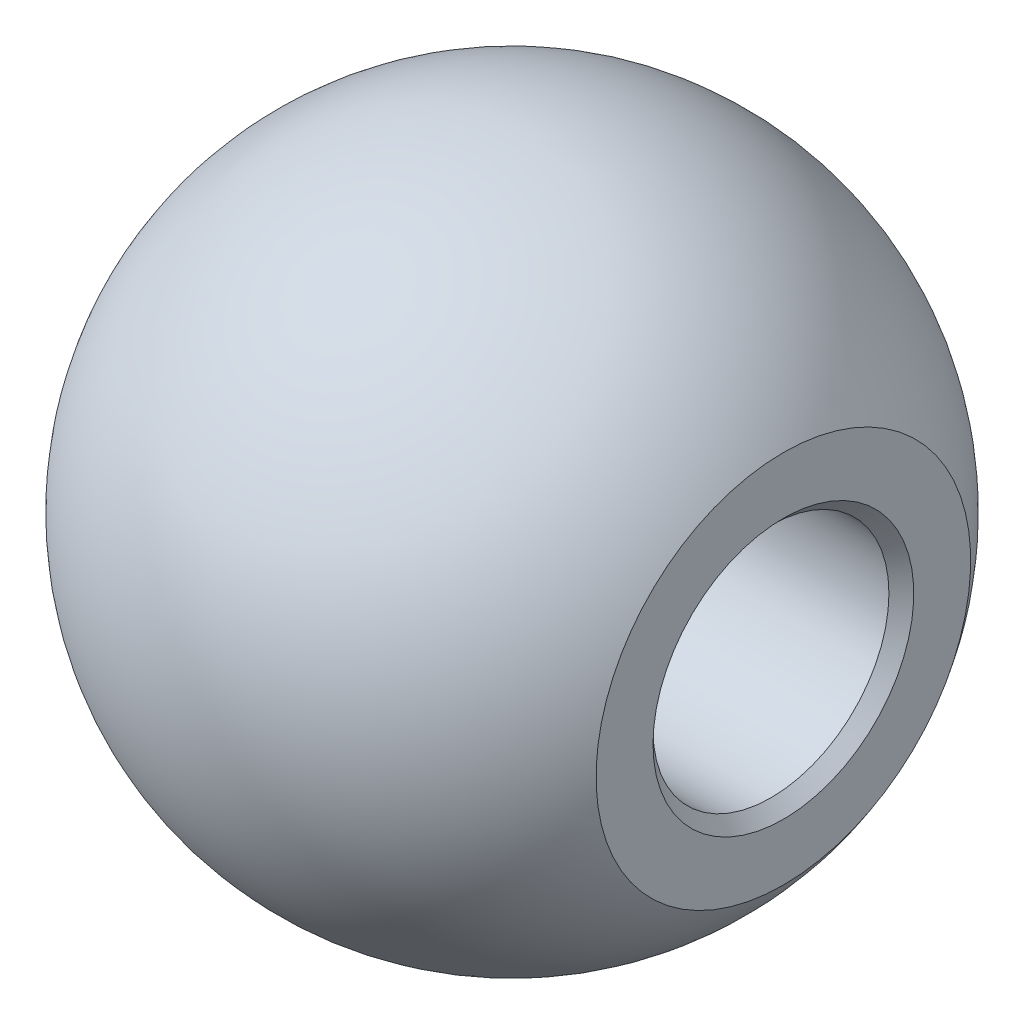
SolidWorks part; units mm, degrees
material "Chrome Stainless Steel"
ref_plane "Front Plane" through (0, 0, 0) normal (0, 0, 1) x (1, 0, 0)
ref_plane "Top Plane" through (0, 0, 0) normal (0, 1, 0) x (1, 0, 0)
ref_plane "Right Plane" through (0, 0, 0) normal (1, 0, 0) x (0, 0, -1)
sketch "Sketch1" plane through (0, 0, 0) normal (0, 0, 1) x (1, 0, 0)
  line L0 (0, 0) -> (5.5499, 0) construction
  line L1 (0, 2.413) -> (5.5499, 2.413)
  line L2 (5.5499, 2.413) -> (5.5499, 3.8309)
  line L3 (0, 2.413) -> (0, 6.7437)
  line L4 (0, 0) -> (0, 2.413) construction
  arc A0 (5.5499, 3.8309) -> (0, 6.7437) centre (0, 0) ccw
  dimension "Ball_Dia" = 13.4874
  dimension "B" = 4.826
  dimension "D2" = 7.6619
  dimension "W" = 11.0998
revolve "Revolve1" add sketch "Sketch1" angle 360 about L0
chamfer "Chamfer1" distance 0.254 angle 45 1 edges at (5.5499, 0, 2.413)
mirror "Mirror1" about plane through (0, 0, 0) normal (1, 0, 0) of bodies 101
